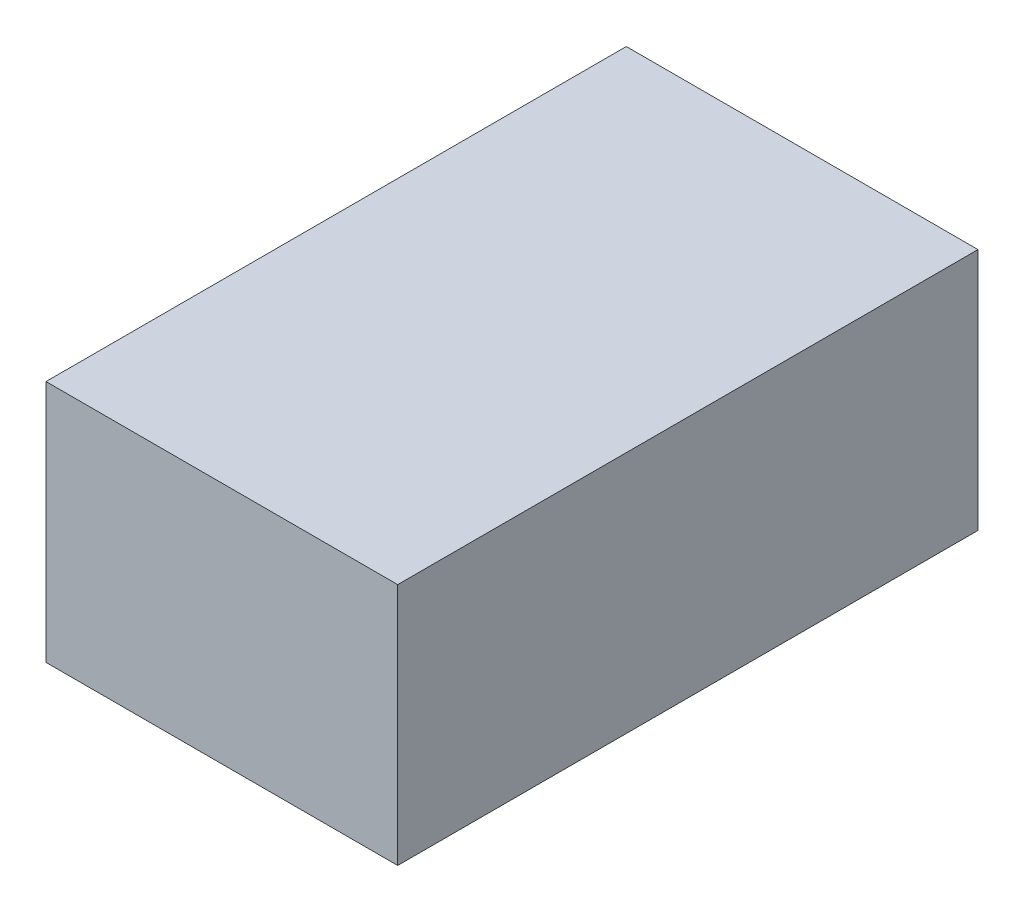
SolidWorks part; units mm, degrees
ref_plane "Front Plane" through (0, 0, 0) normal (0, 0, 1) x (1, 0, 0)
ref_plane "Top Plane" through (0, 0, 0) normal (0, 1, 0) x (1, 0, 0)
ref_plane "Right Plane" through (0, 0, 0) normal (1, 0, 0) x (0, 0, -1)
sketch "Sketch1" plane through (0, 0, 0) normal (0, 0, 1) x (1, 0, 0)
  line L1 (-60, -41.5) -> (60, -41.5)
  line L2 (-60, -41.5) -> (-60, 41.5)
  line L3 (-60, 41.5) -> (60, 41.5)
  line L4 (60, -41.5) -> (60, 41.5)
  line L5 (-60, -41.5) -> (60, 41.5) construction
  line L6 (-60, 41.5) -> (60, -41.5) construction
  point P0 (0, 0)
extrude "Boss-Extrude1" add sketch "Sketch1" along normal blind 198
